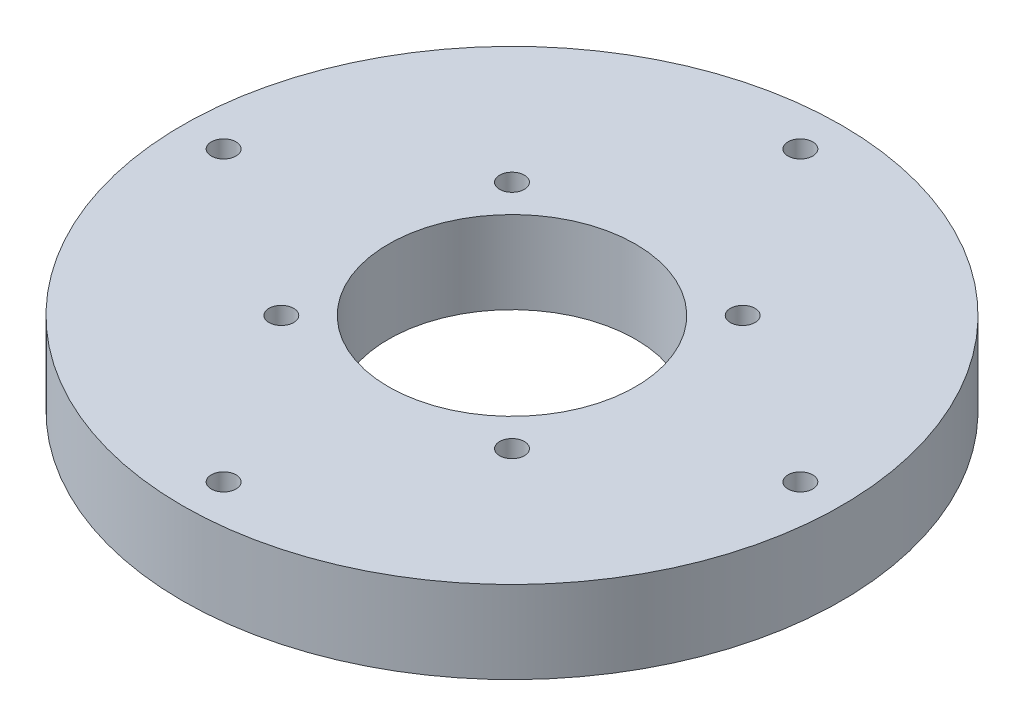
SolidWorks part; units mm, degrees
ref_plane "前视基准面" through (0, 0, 0) normal (0, 0, 1) x (1, 0, 0)
ref_plane "上视基准面" through (0, 0, 0) normal (0, 1, 0) x (1, 0, 0)
ref_plane "右视基准面" through (0, 0, 0) normal (1, 0, 0) x (0, 0, -1)
other "Configuration Table"
sketch "草图1" plane through (0, 0, 0) normal (0, 1, 0) x (1, 0, 0)
  line L22 (-25, -25) -> (25, -25)
  line L23 (-25, -25) -> (-25, 25)
  line L28 (-25, 25) -> (25, 25)
  line L29 (25, -25) -> (25, 25)
  line L37 (-25, -25) -> (25, 25) construction
  line L38 (-25, 25) -> (25, -25) construction
  circle A7 centre (0, 0) radius 7.5
  point P0 (0, 0)
  dimension "D4" = 15
  dimension "D2" = 50
extrude "凸台-拉伸1" add sketch "草图1" along normal blind 5
sketch "草图3" plane through (0, 0, 0) normal (0, -1, 0) x (1, 0, 0)
  circle A4 centre (-7, 7) radius 0.75
  circle A5 centre (7, 7) radius 0.75
  circle A6 centre (7, -7) radius 0.75
  circle A7 centre (-7, -7) radius 0.75
  dimension "D1" = 1.5
extrude "切除-拉伸2" cut sketch "草图3" against normal through all
sketch "草图4" plane through (0, 5, 0) normal (0, 1, 0) x (1, 0, 0)
  line L0 (0, -17.5) -> (0, 17.5)
  line L1 (17.5, 0) -> (-17.5, 0)
  circle A0 centre (0, -17.5) radius 0.75
  circle A1 centre (0, 17.5) radius 0.75
  circle A2 centre (17.5, 0) radius 0.75
  circle A3 centre (-17.5, 0) radius 0.75
  dimension "D2" = 1.5
  dimension "D1" = 35
extrude "切除-拉伸3" cut sketch "草图4" against normal through all contours A2 | A1 | A3 | A0
sketch "草图5" plane through (0, 5, 0) normal (0, 1, 0) x (1, 0, 0)
  circle A0 centre (0, 0) radius 20
  dimension "D1" = 40
extrude "切除-拉伸4" cut sketch "草图5" against normal through all flip side to cut
